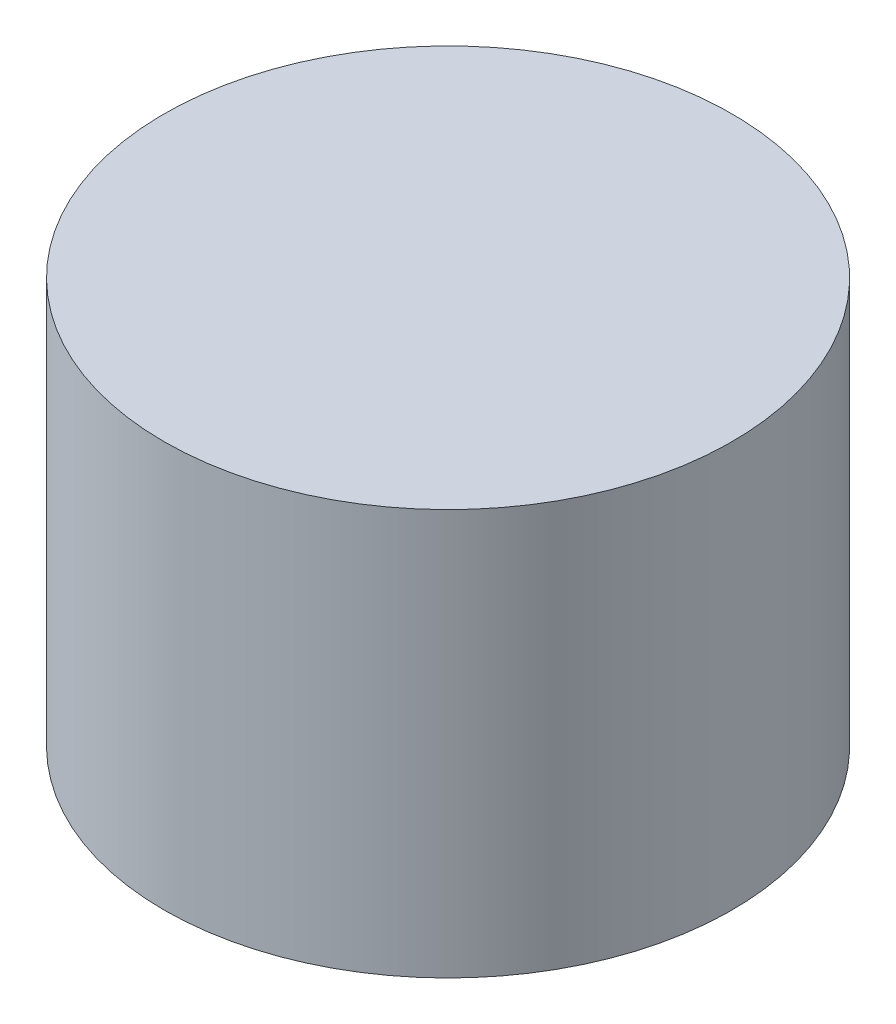
SolidWorks part; units mm, degrees
ref_plane "Front Plane" through (0, 0, 0) normal (0, 0, 1) x (1, 0, 0)
ref_plane "Top Plane" through (0, 0, 0) normal (0, 1, 0) x (1, 0, 0)
ref_plane "Right Plane" through (0, 0, 0) normal (1, 0, 0) x (0, 0, -1)
sketch "Sketch1" plane through (0, 0, 0) normal (0, 1, 0) x (1, 0, 0)
  circle A0 centre (0, 0) radius 3.5
extrude "Boss-Extrude1" add sketch "Sketch1" along normal blind 5
